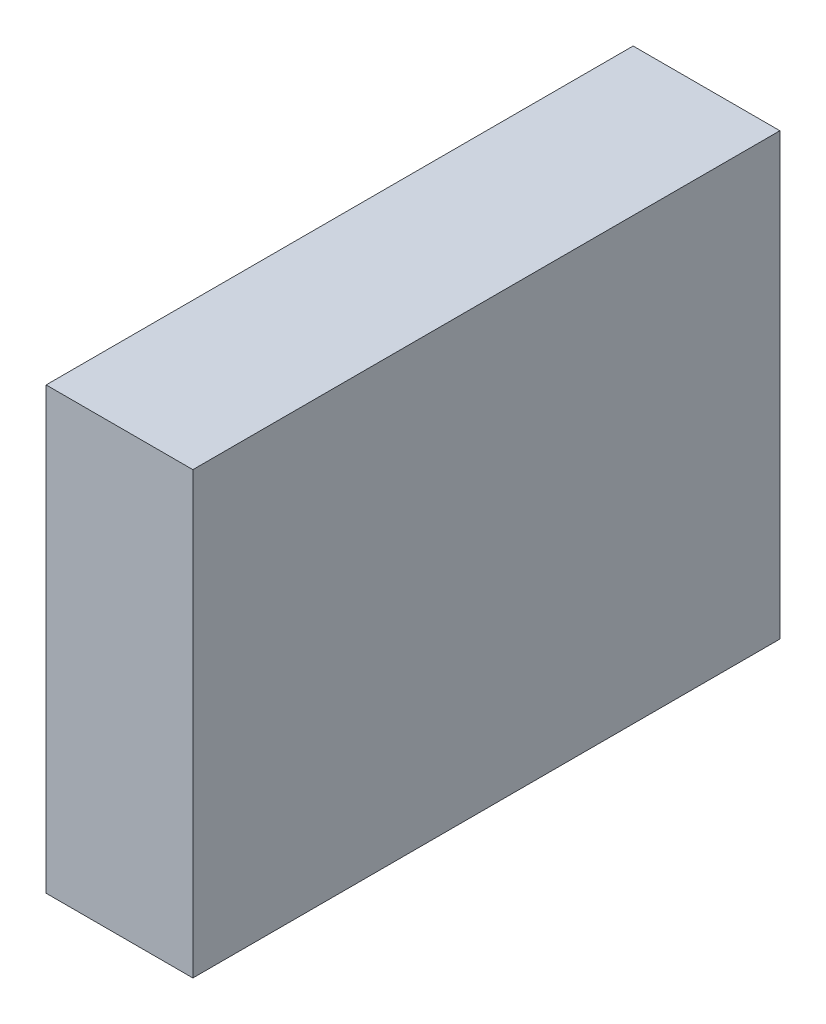
SolidWorks part; units mm, degrees
ref_plane "Front Plane" through (0, 0, 0) normal (0, 0, 1) x (1, 0, 0)
ref_plane "Top Plane" through (0, 0, 0) normal (0, 1, 0) x (1, 0, 0)
ref_plane "Right Plane" through (0, 0, 0) normal (1, 0, 0) x (0, 0, -1)
sketch "Sketch1" plane through (0, 0, 0) normal (0, 0, 1) x (1, 0, 0)
  line L1 (0, 0) -> (25.4, 0)
  line L2 (0, 0) -> (0, 76.2)
  line L3 (0, 76.2) -> (25.4, 76.2)
  line L4 (25.4, 0) -> (25.4, 76.2)
  dimension "D1" = 25.4
  dimension "D2" = 76.2
extrude "Boss-Extrude1" add sketch "Sketch1" along normal blind 101.6
equation "\"baseplate_thickness\"=0.47"
equation "\"baseplate_length\"= 12"
equation "\"baseplate_width\"= 4"
equation "\"rail_width\"= 1"
equation "\"rail_radial_clearance\"= 0.25"
equation "\"slider_width\"= 2"
equation "\"slider_length\"= 4"
equation "\"slider_thickness\"= 1"
equation "\"side_radial_clearance\"= 0.01"
equation "\"front_radial_clearance\"= 0.01"
equation "\"side_plate_width\"= (\"baseplate_width\" - \"slider_width\" - ( 2 * \"side_radial_clearance\" ))/2"
equation "\"side_plate_height\"= \"slider_thickness\" + ( 2 * \"front_radial_clearance\" )"
equation "\"keeper_plate_thickness\"= 0.5"
equation "\"keeper_plate_width\"= (\"baseplate_width\" - \"rail_width\" -  2 * \"rail_radial_clearance\")/2"
equation "\"D1@Sketch1\"=\"rail_width\""
equation "\"rail_height\"= 3"
equation "\"D2@Sketch1\"=\"rail_height\""
equation "\"D1@Boss-Extrude1\"=\"slider_length\""
